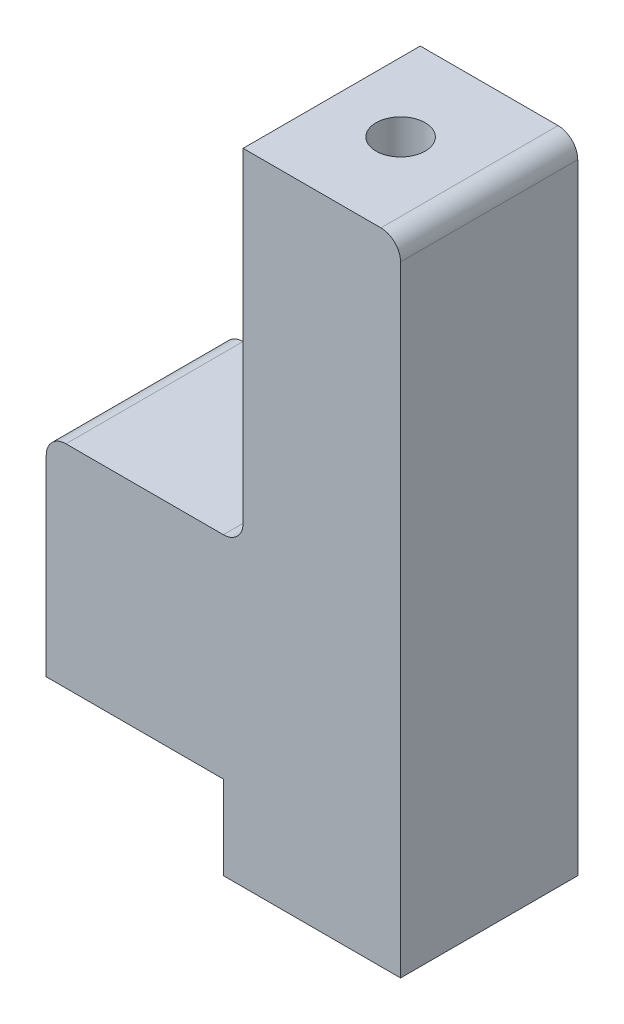
SolidWorks part; units mm, degrees
ref_plane "Front" through (0, 0, 0) normal (0, 0, 1) x (1, 0, 0)
ref_plane "Top" through (0, 0, 0) normal (0, 1, 0) x (1, 0, 0)
ref_plane "Right" through (0, 0, 0) normal (1, 0, 0) x (0, 0, -1)
sketch "Sketch1" plane through (0, 0, 0) normal (0, 1, 0) x (1, 0, 0)
  line L1 (-4.5, -4.5) -> (4.5, -4.5)
  line L2 (-4.5, -4.5) -> (-4.5, 4.5)
  line L3 (-4.5, 4.5) -> (4.5, 4.5)
  line L4 (4.5, -4.5) -> (4.5, 4.5)
  line L5 (-4.5, -4.5) -> (4.5, 4.5) construction
  line L6 (-4.5, 4.5) -> (4.5, -4.5) construction
  point P0 (0, 0)
  dimension "D1" = 9
  dimension "D2" = 9
extrude "Boss-Extrude1" add sketch "Sketch1" along normal blind 15
sketch "Sketch2" plane through (0, 0, 0) normal (0, -1, 0) x (1, 0, 0)
  circle A0 centre (0, 0) radius 3.75
  dimension "D1" = 7.5
extrude "Cut-Extrude1" cut sketch "Sketch2" against normal blind 5
sketch "Sketch3" plane through (0, 15, 0) normal (0, 1, 0) x (1, 0, 0)
  line L1 (4.5, 4.5) -> (13.5, 4.5)
  line L2 (4.5, 4.5) -> (4.5, -4.5)
  line L3 (4.5, -4.5) -> (13.5, -4.5)
  line L4 (13.5, 4.5) -> (13.5, -4.5)
  dimension "D1" = 9
  dimension "D2" = 9
extrude "Boss-Extrude2" add sketch "Sketch3" against normal blind 20
sketch "Sketch5" plane through (-4.5, 0, 0) normal (-1, 0, 0) x (0, 0, 1)
  line L0 (4.5, 0) -> (3.75, 0)
  line L1 (-4.5, 0) -> (4.5, 0) construction
  line L2 (4.5, 0) -> (4.5, -0.75)
  line L3 (4.5, -5) -> (4.5, 0) construction
  line L4 (3.75, 0) -> (3.75, -0.75) construction
  line L5 (3.75, -0.75) -> (4.5, -0.75) construction
  arc A1 (4.5, -0.75) -> (3.75, 0) centre (3.75, -0.75) ccw
  line M6 (-4.5, 0) -> (4.5, 0)
  dimension "D1" = 0.75
extrude "Boss-Extrude3" add sketch "Sketch5" against normal up to surface (9 mm away) contours A1 L2 M6 up to face at (4.5, -2.5, 0)
sketch "Sketch6" plane through (0, 15, 0) normal (0, 1, 0) x (1, 0, 0)
  line L0 (-4.5, -4.5) -> (13.5, -4.5) construction
  line L1 (-4.5, 4.5) -> (5.5, 4.5)
  line L2 (-4.5, 4.5) -> (-4.5, -4.5)
  line L3 (-4.5, -4.5) -> (5.5, -4.5)
  line L4 (5.5, 4.5) -> (5.5, -4.5)
  dimension "D1" = 10
extrude "Cut-Extrude3" cut sketch "Sketch6" against normal blind 5
fillet "Fillet2" radius 1 2 edges at (5.5, 10, 0) (-4.5, 10, 0)
sketch "Sketch7" plane through (0, 15, 0) normal (0, 1, 0) x (1, 0, 0)
  line L1 (5.5, 4.5) -> (13.5, 4.5)
  line L2 (5.5, 4.5) -> (5.5, -4.5)
  line L3 (5.5, -4.5) -> (13.5, -4.5)
  line L4 (13.5, 4.5) -> (13.5, -4.5)
extrude "Boss-Extrude4" add sketch "Sketch7" along normal blind 12.5
sketch "Sketch4" plane through (0, -5, 0) normal (0, -1, 0) x (1, 0, 0)
  line L0 (4.5, 4.5) -> (13.5, -4.5) construction
  line L1 (4.5, -4.5) -> (13.5, 4.5) construction
  circle A0 centre (9, 0) radius 1.25
  dimension "D1" = 2.5
extrude "Cut-Extrude2" cut sketch "Sketch4" against normal through all
fillet "Fillet3" radius 1 1 edges at (13.5, 27.5, 0)
